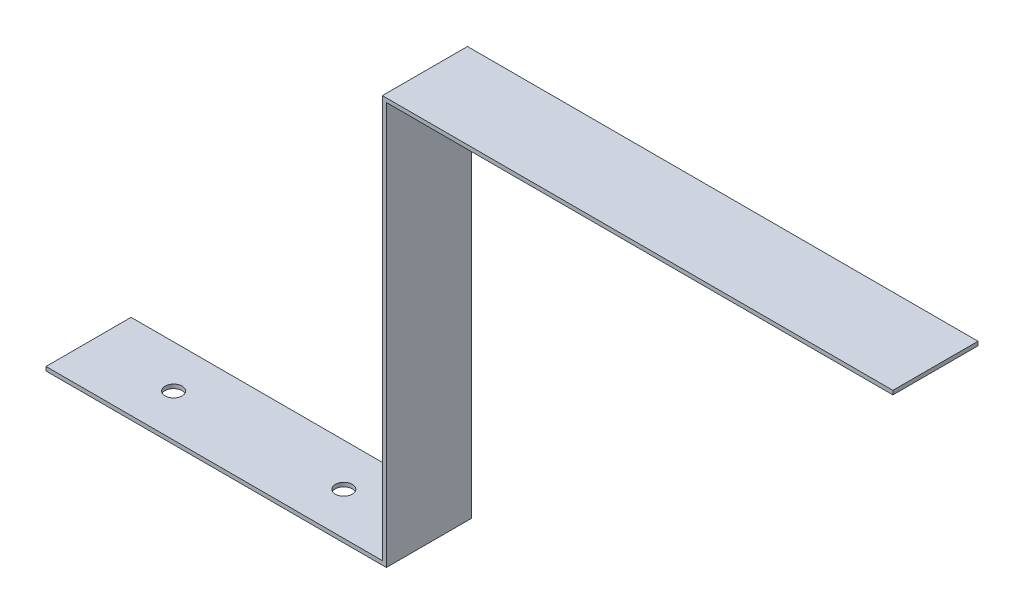
SolidWorks part; units mm, degrees
ref_plane "Front Plane" through (0, 0, 0) normal (0, 0, 1) x (1, 0, 0)
ref_plane "Top Plane" through (0, 0, 0) normal (0, 1, 0) x (1, 0, 0)
ref_plane "Right Plane" through (0, 0, 0) normal (1, 0, 0) x (0, 0, -1)
sketch "Sketch1" plane through (0, 0, 0) normal (0, 0, 1) x (1, 0, 0)
  line L0 (0, 0) -> (60, 0)
  line L1 (60, 0) -> (60, 71)
  line L2 (60, 71) -> (149.3, 71)
  line L3 (149.3, 71) -> (149.3, 71.7)
  line L4 (149.3, 71.7) -> (59.3, 71.7)
  line L5 (59.3, 71.7) -> (59.3, 0.7)
  line L6 (59.3, 0.7) -> (0, 0.7)
  line L7 (0, 0.7) -> (0, 0)
  dimension "D1" = 71
  dimension "D2" = 60
  dimension "D3" = 0.7
  dimension "D4" = 0.7
  dimension "D5" = 0.7
  dimension "D6" = 90
extrude "Boss-Extrude1" add sketch "Sketch1" along normal blind 15
sketch "Sketch2" plane through (0, 0.7, 0) normal (0, 1, 0) x (1, 0, 0)
  line L0 (0, -7.5) -> (59.3, -7.5) construction
  line L1 (0, -15) -> (0, 0) construction
  line L2 (59.3, -15) -> (59.3, 0) construction
  circle A0 centre (15, -7.5) radius 1.5
  circle A1 centre (45, -7.5) radius 1.5
  dimension "D1" = 3
  dimension "D2" = 15
  dimension "D4" = 30
extrude "Cut-Extrude1" cut sketch "Sketch2" against normal through all
